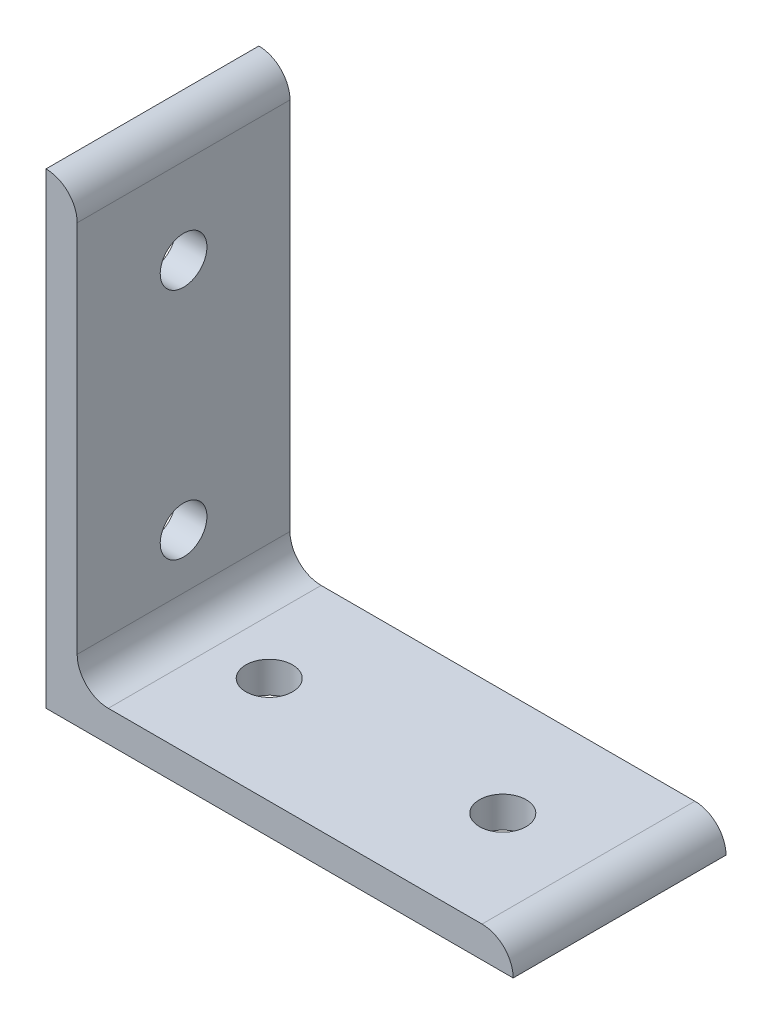
SolidWorks part; units mm, degrees
ref_plane "Front Plane" through (0, 0, 0) normal (0, 0, 1) x (1, 0, 0)
ref_plane "Top Plane" through (0, 0, 0) normal (0, 1, 0) x (1, 0, 0)
ref_plane "Right Plane" through (0, 0, 0) normal (1, 0, 0) x (0, 0, -1)
sketch "Sketch1" plane through (0, 0, 0) normal (0, 0, 1) x (1, 0, 0)
  line L0 (0, 0) -> (0, 90)
  line L1 (6, 84) -> (6, 90) construction
  line L2 (6, 84) -> (6, 12)
  line L3 (12, 6) -> (84, 6)
  line L4 (6, 90) -> (0, 90) construction
  line L5 (90, 0) -> (0, 0)
  line L6 (84, 6) -> (90, 6) construction
  line L7 (90, 6) -> (90, 0) construction
  arc A0 (6, 84) -> (0, 90) centre (0, 84) ccw
  arc A1 (90, 0) -> (84, 6) centre (84, 0) ccw
  arc A2 (6, 12) -> (12, 6) centre (12, 12) ccw
  point P10 (6, 87)
  dimension "E" = 6
  dimension "D" = 6
  dimension "C" = 90
  dimension "B" = 90
extrude "Boss-Extrude1" add sketch "Sketch1" along normal mid plane 41
sketch "Sketch2" plane through (0, 0, 0) normal (0, 1, 0) x (1, 0, 0)
  line L0 (0, 0) -> (22.5, 0) construction
  line L1 (22.5, 0) -> (67.5, 0) construction
  circle A0 centre (22.5, 0) radius 4.5
  circle A1 centre (67.5, 0) radius 4.5
extrude "Cut-Extrude1" cut sketch "Sketch2" along normal through all
sketch "Sketch3" plane through (0, 0, 0) normal (1, 0, 0) x (0, 0, -1)
  line L0 (0, 0) -> (0, 22.5) construction
  line L1 (0, 22.5) -> (0, 67.5) construction
  circle A0 centre (0, 22.5) radius 4.5
  circle A1 centre (0, 67.5) radius 4.5
  dimension "D1" = 22.5
  dimension "D2" = 45
extrude "Cut-Extrude2" cut sketch "Sketch3" along normal through all
equation "\"E@Sketch3\" = \"E@Sketch2\""
equation "\"D1@Sketch3\" = \"D1@Sketch2\""
equation "\"D2@Sketch3\" = \"D2@Sketch2\""
